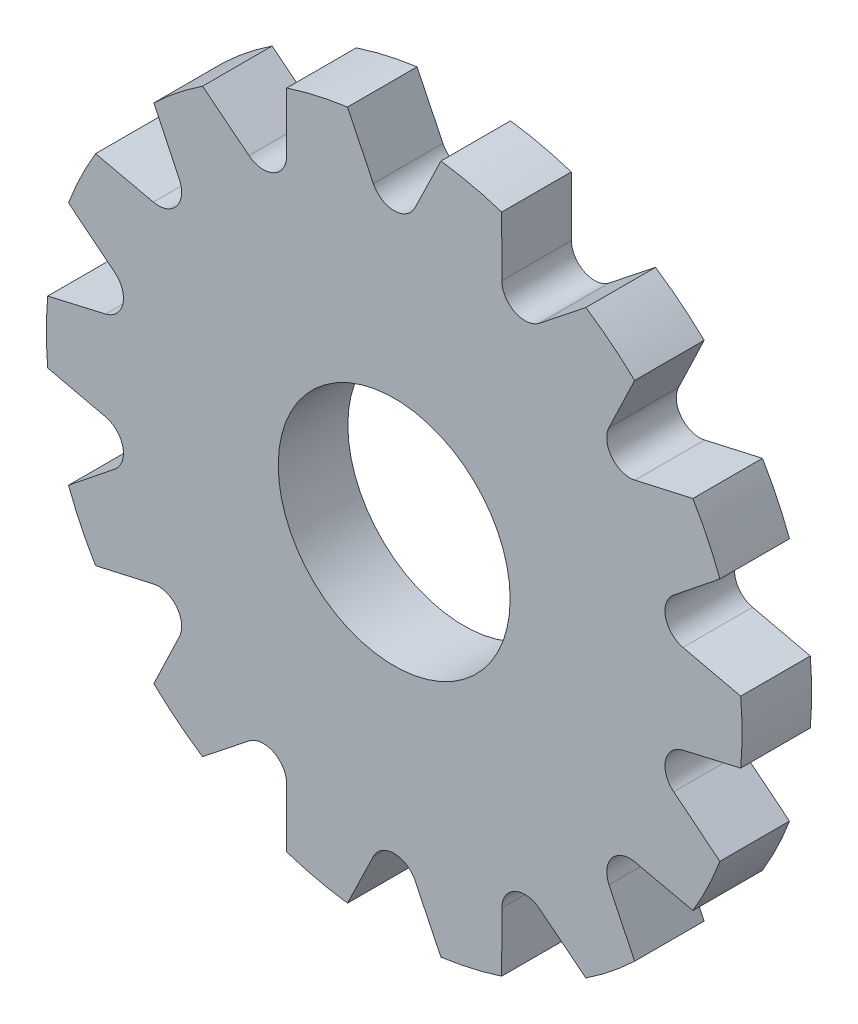
SolidWorks part; units mm, degrees
ref_plane "Front Plane" through (0, 0, 0) normal (0, 0, 1) x (1, 0, 0)
ref_plane "Top Plane" through (0, 0, 0) normal (0, 1, 0) x (1, 0, 0)
ref_plane "Right Plane" through (0, 0, 0) normal (1, 0, 0) x (0, 0, -1)
sketch "Sketch1" plane through (0, 0, 0) normal (0, 0, 1) x (1, 0, 0)
  circle A0 centre (0, 0) radius 10
  circle A1 centre (0, 0) radius 30
  dimension "D1" = 20
  dimension "D2" = 60
extrude "Boss-Extrude1" add sketch "Sketch1" along normal blind 6
sketch "Sketch2" plane through (0, 0, 6) normal (0, 0, 1) x (1, 0, 0)
  line L0 (0, 30) -> (0, 34.7816) construction
  line L1 (-4.0287, 29.7283) -> (-1.7999, 25.128)
  line L2 (4.0287, 29.7283) -> (1.7999, 25.128)
  circle A0 centre (0, 0) radius 30 construction
  arc A1 (4.0287, 29.7283) -> (-4.0287, 29.7283) centre (0, 0) ccw
  arc A2 (-1.7999, 25.128) -> (1.7999, 25.128) centre (0, 26) ccw
  dimension "D1" = 4
  dimension "D2" = 4
  dimension "D3" = 25.85
  dimension "D4" = 25.85
extrude "Cut-Extrude1" cut sketch "Sketch2" against normal blind 6
pattern_circular "CirPattern1" count 14 over 360 about axis through (0, 0, 0) along (0, 0, 1) of "Cut-Extrude1"
